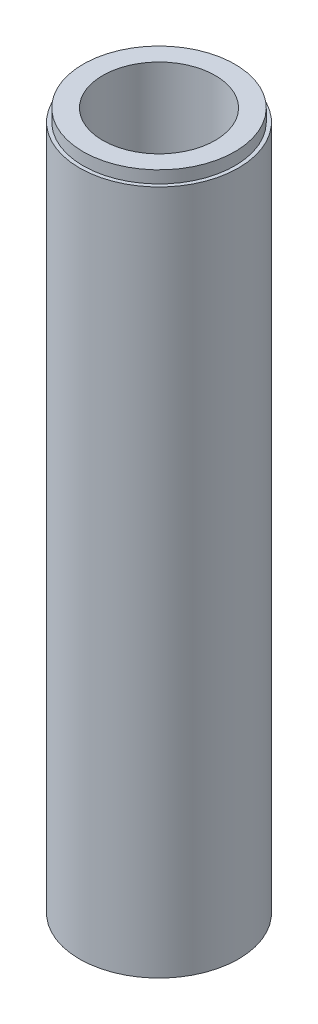
SolidWorks part; units mm, degrees
ref_plane "Спереди" through (0, 0, 0) normal (0, 0, 1) x (1, 0, 0)
ref_plane "Сверху" through (0, 0, 0) normal (0, 1, 0) x (1, 0, 0)
ref_plane "Справа" through (0, 0, 0) normal (1, 0, 0) x (0, 0, -1)
sketch "Эскиз1" plane through (0, 0, 0) normal (0, 1, 0) x (1, 0, 0)
  circle A0 centre (0, 0) radius 2.3
  circle A1 centre (0, 0) radius 3.25
  dimension "D1" = 4.6
  dimension "D2" = 6.5
extrude "Бобышка-Вытянуть1" add sketch "Эскиз1" along normal blind 28
sketch "Эскиз2" plane through (0, 28, 0) normal (0, 1, 0) x (1, 0, 0)
  circle A0 centre (0, 0) radius 2.3
  circle A1 centre (0, 0) radius 3.1
  dimension "D1" = 6.2
extrude "Бобышка-Вытянуть2" add sketch "Эскиз2" along normal blind 0.5
